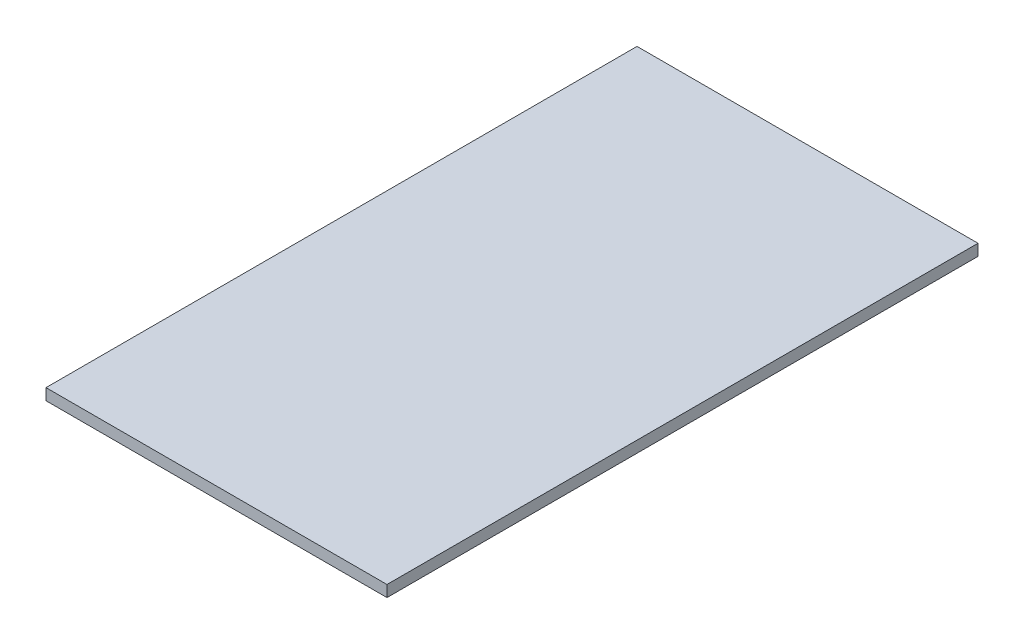
SolidWorks part; units mm, degrees
material "Plain Carbon Steel"
ref_plane "Front Plane" through (0, 0, 0) normal (0, 0, 1) x (1, 0, 0)
ref_plane "Top Plane" through (0, 0, 0) normal (0, 1, 0) x (1, 0, 0)
ref_plane "Right Plane" through (0, 0, 0) normal (1, 0, 0) x (0, 0, -1)
sketch "Sketch1" plane through (0, 29.1433, 0) normal (0, -1, 0) x (1, 0, 0)
  line L1 (-30.3006, 338.4331) -> (-330.3006, 338.4331)
  line L2 (-30.3006, 338.4331) -> (-30.3006, -181.5669)
  line L3 (-30.3006, -181.5669) -> (-330.3006, -181.5669)
  line L4 (-330.3006, 338.4331) -> (-330.3006, -181.5669)
extrude "Boss-Extrude1" add sketch "Sketch1" along normal blind 10
sketch "Centerlines" plane through (0, 29.1433, 0) normal (0, 1, 0) x (1, 0, 0)
  line L0 (-180.3006, 181.5669) -> (-180.3006, -338.4331) construction
  line L1 (-330.3006, 181.5669) -> (-30.3006, 181.5669) construction
  line L2 (-30.3006, -338.4331) -> (-330.3006, -338.4331) construction
  line L3 (-30.3006, -78.4331) -> (-330.3006, -78.4331) construction
  line L4 (-30.3006, 181.5669) -> (-30.3006, -338.4331) construction
  line L5 (-330.3006, -338.4331) -> (-330.3006, 181.5669) construction
  point P12 (-180.3006, -78.4331)
